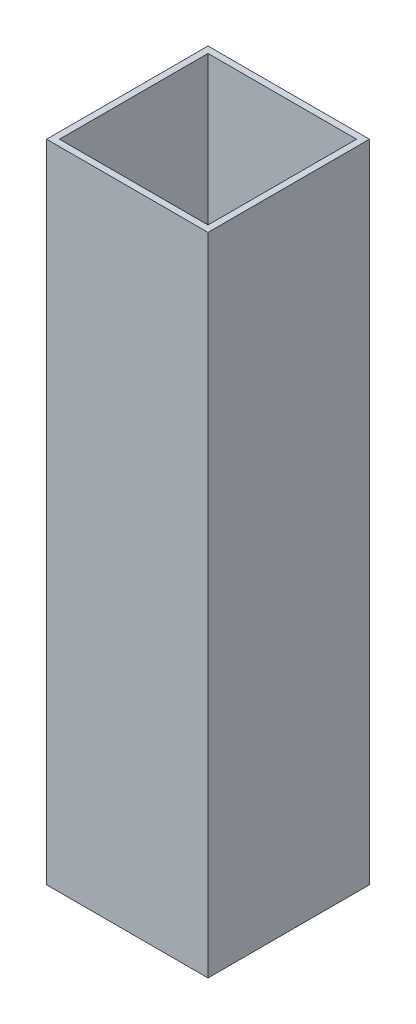
SolidWorks part; units mm, degrees
ref_plane "Front Plane" through (0, 0, 0) normal (0, 0, 1) x (1, 0, 0)
ref_plane "Top Plane" through (0, 0, 0) normal (0, 1, 0) x (1, 0, 0)
ref_plane "Right Plane" through (0, 0, 0) normal (1, 0, 0) x (0, 0, -1)
sketch "Sketch1" plane through (0, 0, 0) normal (0, 1, 0) x (1, 0, 0)
  line L0 (-23, 23) -> (23, 23)
  line L1 (-25, -25) -> (25, -25)
  line L2 (-25, -25) -> (-25, 25)
  line L3 (-25, 25) -> (25, 25)
  line L4 (25, -25) -> (25, 25)
  line L5 (-25, -25) -> (25, 25) construction
  line L6 (-25, 25) -> (25, -25) construction
  line L7 (23, -23) -> (23, 23)
  line L8 (-23, -23) -> (23, -23)
  line L9 (-23, -23) -> (-23, 23)
  point P0 (0, 0)
  dimension "D1" = 50
  dimension "D2" = 2
extrude "Boss-Extrude1" add sketch "Sketch1" along normal blind 200
